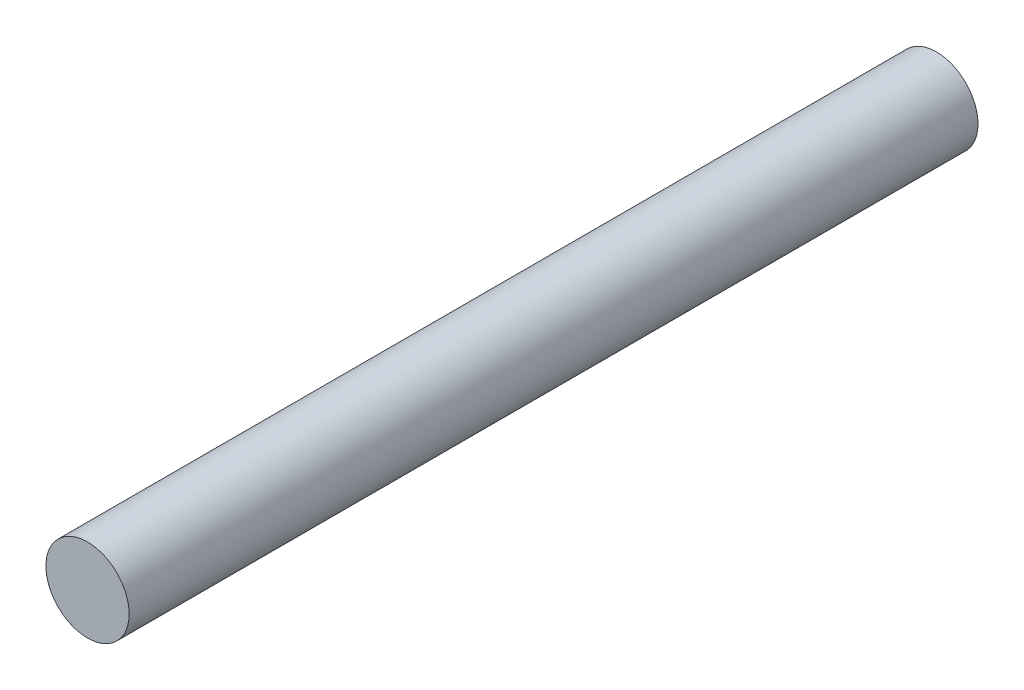
SolidWorks part; units mm, degrees
ref_plane "Front Plane" through (0, 0, 0) normal (0, 0, 1) x (1, 0, 0)
ref_plane "Top Plane" through (0, 0, 0) normal (0, 1, 0) x (1, 0, 0)
ref_plane "Right Plane" through (0, 0, 0) normal (1, 0, 0) x (0, 0, -1)
sketch "Sketch1" plane through (0, 0, 0) normal (1, 0, 0) x (0, 0, -1)
  line L0 (55, 0) -> (-55, 0) construction
  line L1 (-25.5, 0) -> (25.5, 0)
  line L2 (-25.5, 0) -> (-25.5, 2.5)
  line L3 (-25.5, 2.5) -> (25.5, 2.5)
  line L4 (25.5, 0) -> (25.5, 2.5)
  line L5 (0, -11.3439) -> (0, 19.3783) construction
  line L6 (0, 55) -> (0, -55) construction
  dimension "D1" = 51
  dimension "D2" = 2.5
revolve "Revolve1" add sketch "Sketch1" angle 360 about L1
